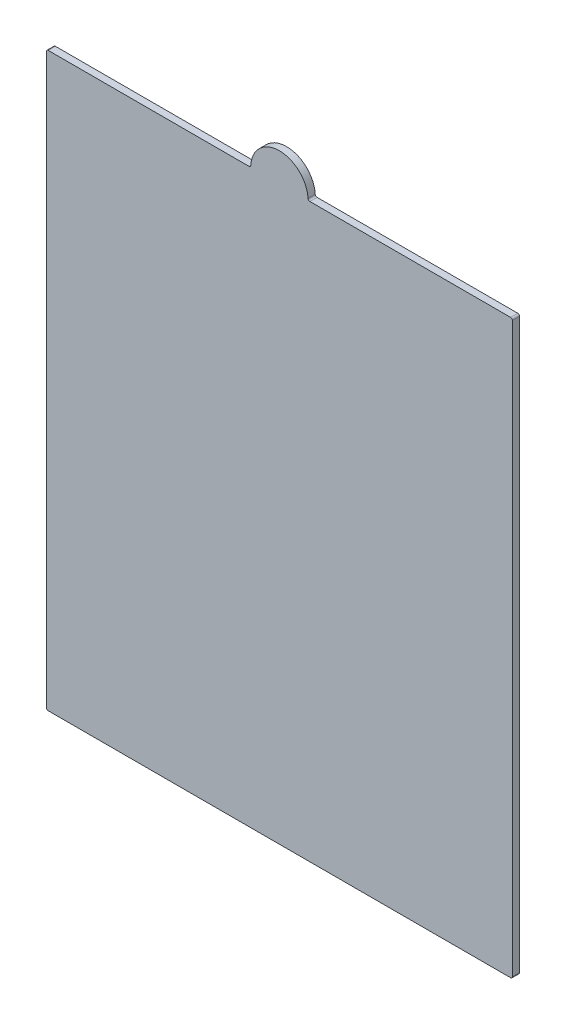
SolidWorks part; units mm, degrees
material "Acrylic (Medium-high impact)"
ref_plane "Front Plane" through (0, 0, 0) normal (0, 0, 1) x (1, 0, 0)
ref_plane "Top Plane" through (0, 0, 0) normal (0, 1, 0) x (1, 0, 0)
ref_plane "Right Plane" through (0, 0, 0) normal (1, 0, 0) x (0, 0, -1)
sketch "Sketch1" plane through (0, 0, 0) normal (0, 0, 1) x (1, 0, 0)
  line L1 (0, 0) -> (206.253, 0)
  line L2 (0, 0) -> (0, 253.103)
  line L3 (0, 253.103) -> (206.253, 253.103)
  line L4 (206.253, 0) -> (206.253, 253.103)
  dimension "D1" = 253.103
  dimension "D2" = 206.253
extrude "Boss-Extrude1" add sketch "Sketch1" along normal blind 3.175
sketch "Sketch4" [suppressed] plane through (0, 0, 3.175) normal (0, 0, 1) x (1, 0, 0)
  line L0 (0, 0) -> (206.253, 0) construction
  line L1 (-25.4, -25.4) -> (1193.8, -25.4)
  line L2 (-25.4, -25.4) -> (-25.4, 1193.8)
  line L3 (-25.4, 1193.8) -> (1193.8, 1193.8)
  line L4 (1193.8, -25.4) -> (1193.8, 1193.8)
  line L5 (0, 253.103) -> (0, 0) construction
  dimension "D1" = 25.4
  dimension "D2" = 25.4
  dimension "D3" = 1219.2
sketch "Sketch3" plane through (0, 0, 0) normal (0, 0, 1) x (1, 0, 0)
  line L0 (206.253, 253.103) -> (0, 253.103) construction
  line L1 (90.4265, 253.103) -> (115.8265, 253.103)
  line L2 (103.1265, 0) -> (103.1265, 265.803) construction
  line L3 (0, 0) -> (206.253, 0) construction
  arc A0 (115.8265, 253.103) -> (90.4265, 253.103) centre (103.1265, 253.103) ccw
  point P9 (103.1265, 265.803)
  dimension "D1" = 25.4
extrude "Boss-Extrude3" add sketch "Sketch3" along normal blind 3.175
fillet "Fillet1" radius 0.7937 6 edges at (0, 0, 1.5875) (206.253, 0, 1.5875) (206.253, 253.103, 1.5875) (0, 253.103, 1.5875) (90.4265, 253.103, 1.5875) (115.8265, 253.103, 1.5875)
